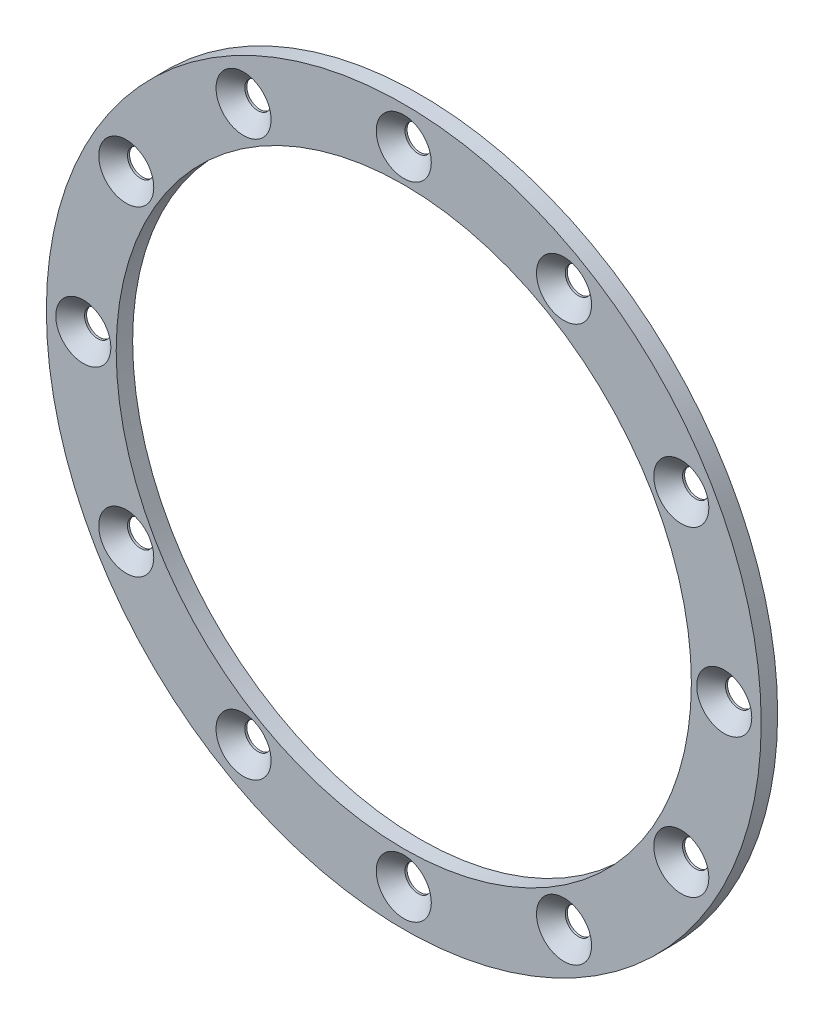
SolidWorks part; units mm, degrees
material "6061 Alloy"
ref_plane "Front Plane" through (0, 0, 0) normal (0, 0, 1) x (1, 0, 0)
ref_plane "Top Plane" through (0, 0, 0) normal (0, 1, 0) x (1, 0, 0)
ref_plane "Right Plane" through (0, 0, 0) normal (1, 0, 0) x (0, 0, -1)
sketch "Sketch1" plane through (0, 0, 0) normal (0, 0, 1) x (1, 0, 0)
  circle A0 centre (0, 0) radius 43.5
  circle A1 centre (0, 0) radius 35
  dimension "D1" = 87
  dimension "D2" = 70
extrude "Boss-Extrude1" add sketch "Sketch1" along normal blind 2
sketch "Sketch2" plane through (0, 0, 2) normal (0, 0, 1) x (1, 0, 0)
  line L0 (0, 0) -> (0, 43.5) construction
  circle A0 centre (0, 0) radius 43.5 construction
  circle A1 centre (0, 0) radius 39 construction
  circle A2 centre (0, 39) radius 1.5
  dimension "D1" = 78
  dimension "D2" = 3
extrude "Cut-Extrude1" cut sketch "Sketch2" against normal blind 10
pattern_circular "CirPattern1" count 12 over 360 about axis through (0, 0, 0) along (0, 0, 1) of "Cut-Extrude1"
hole_wizard "CSK for M3 Flat Head Machine Screw1" positions "Sketch3" profile "Sketch4" countersink size "M3" standard "ANSI Metric" end condition through all
sketch "Sketch3" plane through (0, 0, 2) normal (0, 0, 1) x (1, 0, 0)
  point P0 (0, 39)
sketch "Sketch4" plane through (0, 39, 2) normal (1, 0, 0) x (0, -1, 0)
  line L0 (0, 0) -> (0, 2)
  line L1 (0, 2) -> (1.6, 2)
  line L2 (1.6, 2) -> (1.6, 1.75)
  line L3 (1.6, 1.75) -> (3.35, 0)
  line L5 (3.35, 0) -> (0, 0)
  line L6 (-1.6, 1.75) -> (-3.35, 0) construction
  line L11 (0, -6.35) -> (0, 107.95) construction
  dimension "Thru Hole Dia." = 3.2
  dimension "Thru Hole Depth" = 2
  dimension "Near C'Sink Dia." = 6.7
  dimension "Near C'Sink Angle" = 90
pattern_circular "CirPattern2" count 12 over 360 about axis through (0, 0, 0) along (0, 0, 1) of "CSK for M3 Flat Head Machine Screw1"
